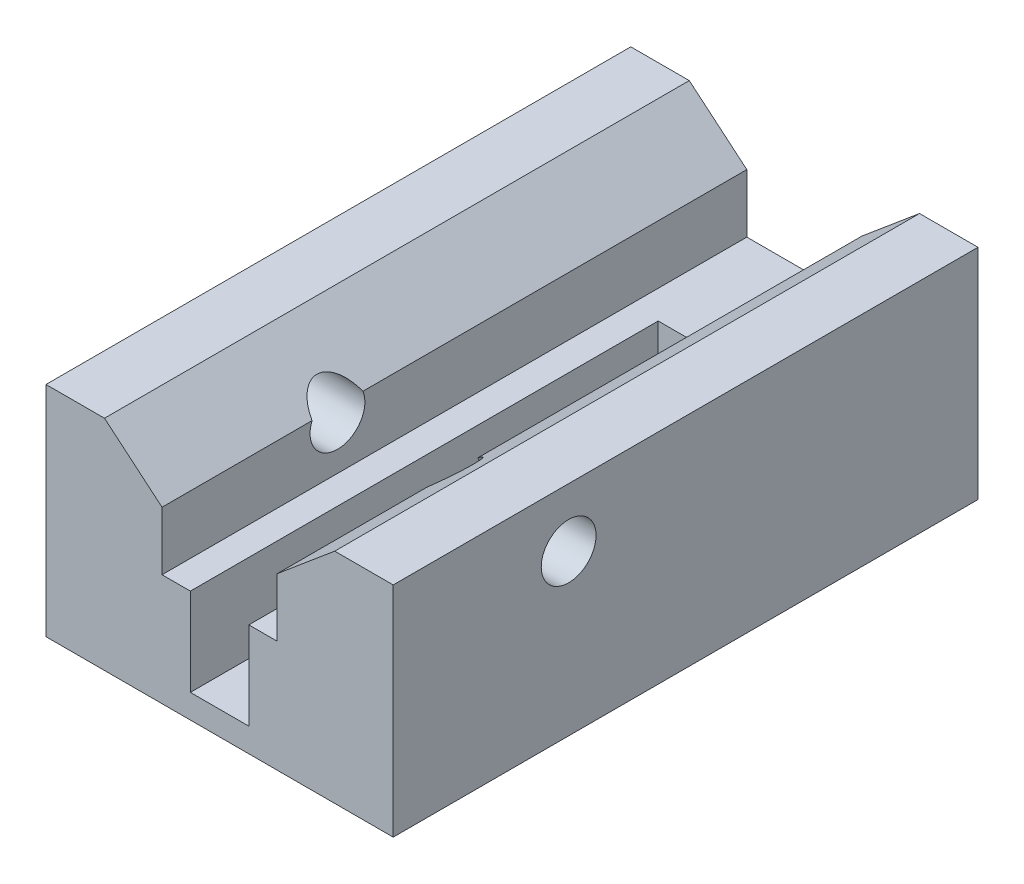
SolidWorks part; units mm, degrees
ref_plane "Front Plane" through (0, 0, 0) normal (0, 0, 1) x (1, 0, 0)
ref_plane "Top Plane" through (0, 0, 0) normal (0, 1, 0) x (1, 0, 0)
ref_plane "Right Plane" through (0, 0, 0) normal (1, 0, 0) x (0, 0, -1)
sketch "Sketch2" plane through (0, 0, 0) normal (0, 0, 1) x (1, 0, 0)
  line L0 (-5, 4.6377) -> (-7.54, 4.6377)
  line L1 (-7.54, -4.8514) -> (7.54, -4.8514)
  line L2 (-7.54, 4.6377) -> (-7.54, -4.8514)
  line L3 (5, 4.6377) -> (2.5, 2.54)
  line L4 (-2.5, 2.54) -> (-2.5, 0)
  line L5 (-2.5, 2.54) -> (-5, 4.6377)
  line L6 (0, -4.8514) -> (0, 0) construction
  line L7 (-2.5, 0) -> (2.5, 0)
  line L8 (2.5, 0) -> (2.5, 2.54)
  line L9 (5, 4.6377) -> (7.54, 4.6377)
  line L10 (7.54, 4.6377) -> (7.54, -4.8514)
  dimension "D1" = 5
  dimension "D2" = 10
  dimension "D3" = 2.54
  dimension "D4" = 130
  dimension "D5" = 2.54
extrude "Boss-Extrude2" add sketch "Sketch2" along normal blind 25.4
sketch "Sketch3" plane through (0, 0, 0) normal (0, 1, 0) x (1, 0, 0)
  line L0 (-1.27, -15.24) -> (-2.5, -15.24) construction
  line L1 (-1.27, -5.08) -> (1.27, -5.08)
  line L2 (-1.27, -5.08) -> (-1.27, -25.4)
  line L3 (-1.27, -25.4) -> (1.27, -25.4)
  line L4 (1.27, -5.08) -> (1.27, -25.4)
  line L5 (-2.5, -25.4) -> (-2.5, 0) construction
  line L6 (1.27, -15.24) -> (2.5, -15.24) construction
  line L7 (2.5, -25.4) -> (2.5, 0) construction
  line L8 (2.5, 0) -> (-2.5, 0) construction
  line L9 (2.5, -25.4) -> (-2.5, -25.4) construction
  dimension "D1" = 2.54
  dimension "D2" = 5.08
extrude "Cut-Extrude1" cut sketch "Sketch3" against normal blind 3.81
sketch "Sketch4" plane through (7.54, 0, 0) normal (1, 0, 0) x (0, 0, -1)
  line L1 (-25.4, -4.8514) -> (-25.4, 4.6377) construction
  line L3 (-25.4, 4.6377) -> (0, 4.6377) construction
  circle A0 centre (-17.78, 2.0977) radius 1.1906
  point P7 (-17.7318, 4.6377)
  point P8 (-18.458, 1.754)
  dimension "D1" = 2.3813
  dimension "D3" = 2.54
  dimension "D2" = 7.62
extrude "Cut-Extrude2" cut sketch "Sketch4" against normal through all
